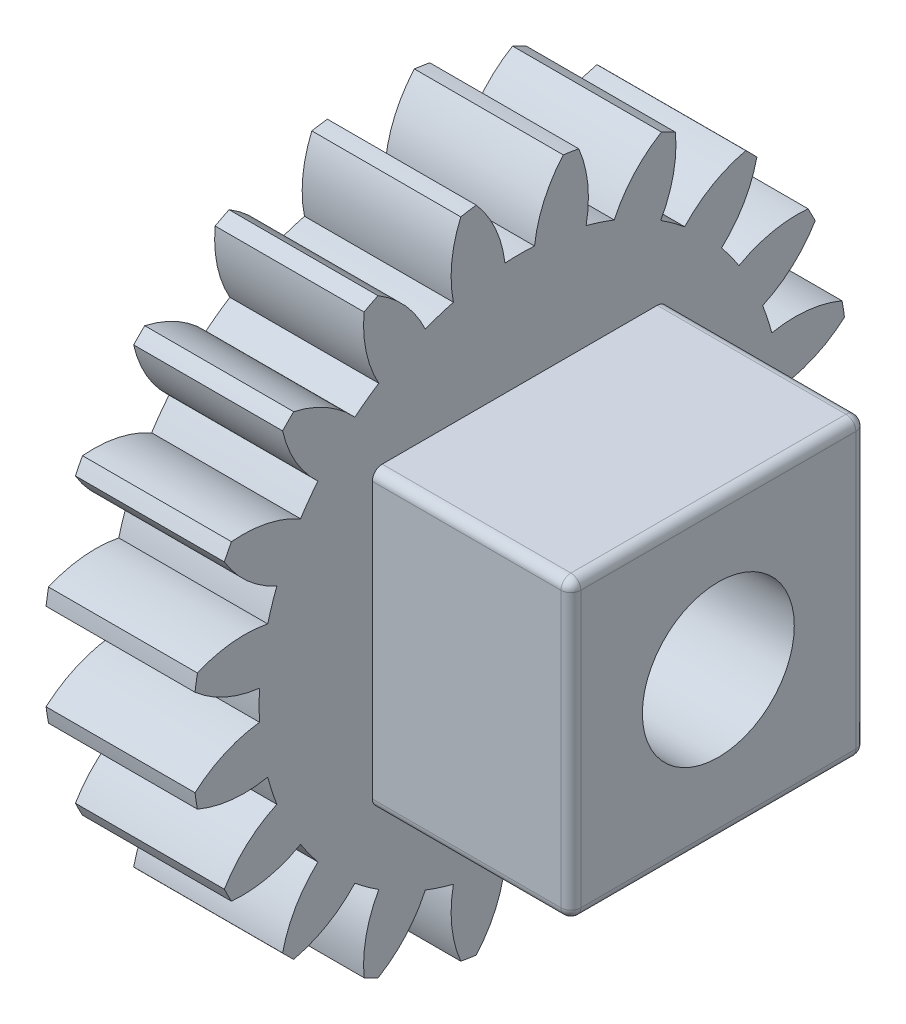
SolidWorks part; units mm, degrees
material "Custom Plastic"
ref_plane "Plane1" through (0, 0, 0) normal (0, 0, 1) x (1, 0, 0)
ref_plane "Plane2" through (0, 0, 0) normal (0, 1, 0) x (1, 0, 0)
ref_plane "Plane3" through (0, 0, 0) normal (1, 0, 0) x (0, 0, -1)
other "Configuration Table"
sketch "HoldingSke" plane through (0, 0, 0) normal (0, 1, 0) x (1, 0, 0)
  line L0 (0, 0) -> (0.3132, -0.114)
  line L1 (-15, 0) -> (100, 0) construction
  line L2 (0, 0) -> (-2.1039, 2.3779)
  line L3 (0, 0) -> (-11.863, 4.5341)
  line L4 (0, 0) -> (8.1152, 2.9537)
  line L5 (0, 0) -> (-46.8476, -17.4728)
  line L6 (0, 0) -> (-12.4344, -8.3896)
  line L7 (-2.1039, 2.3779) -> (8.6586, 51.2059)
  line L8 (-76.2, 54.61) -> (-75.5, 54.61)
  line L9 (-71.009, 38.7566) -> (-53.1078, 45.2721)
  line L10 (-76.2, 71.12) -> (104.1128, 71.12)
  line L11 (0, 0) -> (-15, 0)
  line L12 (-76.2, 101.6) -> (-76.093, 101.6)
  line L13 (24.9733, 27.94) -> (52.9518, 28.4284)
  line L14 (24.9733, 27.94) -> (24.9743, 27.94)
  line L15 (24.9733, 27.94) -> (100.4006, 29.5858)
  line L16 (-63.627, -3) -> (-12.827, -3)
  circle A0 centre (0, 0) radius 2
  circle A1 centre (0, 0) radius 26.249
  circle A2 centre (0, 0) radius 37.5
  circle A3 centre (0, 0) radius 2
  dimension "MHD" = 52.498
  dimension "Hub_dia" = 75
  dimension "Bore" = 4
  dimension "MBD" = 4
  dimension "Num_teeth" = 20
  dimension "Pitch" = 0.3333
  dimension "Overall_len" = 50
  dimension "Show_teeth" = 20
  dimension "Thickness" = 15
  dimension "OAL" = 50.0001
  dimension "T_dim" = 0.7
  dimension "Ap" = 20
  dimension "H" = 19.05
  dimension "Pitch_radius" = 180.3128
  dimension "Width" = 15
  dimension "Backlash" = 0.107
  dimension "Addendum_fac" = 1
  dimension "Dedendum_fac" = 1.25
  dimension "Clearance_fac" = 0.25
  dimension "Dedendum_add" = 0.001
  dimension "Module" = 3
sketch "BasProSke" plane through (0, 0, 0) normal (0, 1, 0) x (1, 0, 0)
  line L0 (-10, 0) -> (60, 0) construction
  line L1 (0, 0) -> (0, 33)
  line L2 (0, 0) -> (15, 0)
  line L3 (15, 0) -> (15, 33)
  line L4 (15, 33) -> (0, 33)
  dimension "Thickness" = 15
  dimension "Diameter" = 66
revolve "Base-Revolve" add sketch "BasProSke" angle 360 about L0
sketch "TooCutSke" plane through (0, 0, 0) normal (1, 0, 0) x (0, 0, -1)
  line L1 (0, 0) -> (0, 107) construction
  line L2 (0, 0) -> (-2.5409, 29.8922) construction
  line L3 (0, 0) -> (-9.3616, 59.1066) construction
  line L4 (-2.5409, 29.8922) -> (-4.6808, 29.5533) construction
  arc A0 (1.4893, 26.2067) -> (-1.4893, 26.2067) centre (0, 0) ccw
  arc A1 (4.4016, 32.7308) -> (-4.4016, 32.7308) centre (0, 0) ccw
  circle A2 centre (0, 0) radius 30 construction
  circle A3 centre (0, 0) radius 28.1908 construction
  arc A4 (-1.4893, 26.2067) -> (-4.4016, 32.7308) centre (-13.4064, 24.799) ccw
  arc A5 (4.4016, 32.7308) -> (1.4893, 26.2067) centre (13.4064, 24.799) ccw
  dimension "Root_dia" = 52.498
  dimension "Overcut_dia" = 66.0508
  dimension "Pitch_dia" = 60
  dimension "Base_dia" = 56.3816
  dimension "Flank_rad" = 12
  dimension "Half_ang" = 9
  dimension "Half_CT" = 2.1665
extrude "ToothCut" cut sketch "TooCutSke" along normal through all
fillet "Breaks" [suppressed] radius 0.06
fillet "RootFillets" [suppressed] radius 0.751
pattern_circular "TeethCuts" count 20 every 18 about axis through (-10, 0, 0) along (1, 0, 0) of "ToothCut", "RootFillets", "Breaks"
sketch "HubNeaOneSke" plane through (0, 0, 0) normal (-1, 0, 0) x (0, 0, 1)
  circle A0 centre (0, 0) radius 26.249
  dimension "Diameter" = 52.498
extrude "HubNearOne" [suppressed] add sketch "HubNeaOneSke" along normal blind 35.0001
sketch "HubNeaBotSke" plane through (0, 0, 0) normal (-1, 0, 0) x (0, 0, 1)
  circle A0 centre (0, 0) radius 26.249
  dimension "Diameter" = 52.498
extrude "HubNearBoth" [suppressed] add sketch "HubNeaBotSke" along normal blind 17.5
ref_plane "FarPln" through (15, 0, 0) normal (1, 0, 0) x (0, 0, -1)
sketch "HubFarSke" plane through (15, 0, 0) normal (1, 0, 0) x (0, 0, -1)
  circle A0 centre (0, 0) radius 26.249
  dimension "Diameter" = 52.498
extrude "HubFar" [suppressed] add sketch "HubFarSke" along normal blind 17.5
sketch "BorSke" plane through (0, 0, 0) normal (1, 0, 0) x (0, 0, -1)
  circle A0 centre (0, 0) radius 2
  dimension "Diameter" = 4
extrude "Bore" cut sketch "BorSke" along normal mid plane 100.0001
sketch "KeySke" plane through (0, 0, 0) normal (1, 0, 0) x (0, 0, -1)
  line L0 (-0.8, 0) -> (-0.8, 2.7)
  line L1 (-0.8, 2.7) -> (0.8, 2.7)
  line L2 (0.8, 2.7) -> (0.8, 0)
  line L3 (0, 0) -> (0, 34) construction
  line L4 (-0.8, 0) -> (0.8, 0)
  dimension "Offset" = 2.7
  dimension "Width" = 1.6
extrude "Keyway" [suppressed] cut sketch "KeySke" along normal mid plane 100.0001
pattern_circular "Keyway2" [suppressed] count 2 every 90 about axis through (-10, 0, 0) along (1, 0, 0)
sketch "Sketch1" plane through (15, 0, 0) normal (1, 0, 0) x (0, 0, -1)
  line L0 (-14.85, 14.85) -> (14.85, -14.85) construction
  line L1 (-14.85, 14.85) -> (14.85, 14.85)
  line L2 (-14.85, 14.85) -> (-14.85, -14.85)
  line L3 (-14.85, -14.85) -> (14.85, -14.85)
  line L4 (14.85, 14.85) -> (14.85, -14.85)
  point P4 (0, 0)
  dimension "D1" = 29.7
extrude "Boss-Extrude1" add sketch "Sketch1" along normal blind 20
sketch "Sketch2" plane through (0, 0, 0) normal (-1, 0, 0) x (0, 0, 1)
  circle A0 centre (0, 0) radius 7.65
  dimension "D1" = 15.3
extrude "Cut-Extrude1" cut sketch "Sketch2" against normal up to surface (35 mm away) contours A0 up to face at (35, 0, 0)
fillet "Fillet2" radius 1 8 edges at (35, 14.85, 0) (35, 0, 14.85) (35, -14.85, 0) (35, 0, -14.85) (25, -14.85, -14.85) (25, 14.85, -14.85) (25, 14.85, 14.85) (25, -14.85, 14.85)
equation "' \"Module@HoldingSke\" = 6.35"
equation "' \"Num_teeth@HoldingSke\" = 12"
equation "' \"Ap@HoldingSke\" =  20"
equation "' \"Ap@HoldingSke\" = 20"
equation "' \"Width@HoldingSke\" = 0.5 * 25.4"
equation "' \"Hub_dia@HoldingSke\"= 1 * 25.4"
equation "' \"Hub_dia@HoldingSke\" = 1 * 25.4"
equation "' \"Overall_len@HoldingSke\" = 1.0 * 25.4"
equation "' \"Bore@HoldingSke\" = 0.75 * 25.4"
equation "' \"T_dim@HoldingSke\" = 0.1 * 25.4"
equation "' \"Width@KeySke\" = 0.25 * 25.4"
equation "' \"Show_teeth@HoldingSke\" = 13"
equation "' \"Backlash@HoldingSke\" = 0.009 * 25.4"
equation "' \"Addendum_fac@HoldingSke\" = 1.0"
equation "' \"Dedendum_fac@HoldingSke\" = 1.25"
equation "' \"Dedendum_add@HoldingSke\" = 0.00005 * 25.4"
equation "' \"Clearance_fac@HoldingSke\" = 0.25"
equation "\"Pitch@HoldingSke\" = 1 / \"Module@HoldingSke\""
equation "\"Overcut_dia@TooCutSke\" = (\"Num_teeth@HoldingSke\" + 2 * \"Addendum_fac@HoldingSke\") / \"Pitch@HoldingSke\" + 0.002 * 25.4"
equation "\"Pitch_dia@TooCutSke\" = \"Num_teeth@HoldingSke\" / \"Pitch@HoldingSke\""
equation "\"Base_dia@TooCutSke\" = \"Num_teeth@HoldingSke\" / \"Pitch@HoldingSke\" * cos((\"Ap@HoldingSke\"  * 3.14159265 / 180))"
equation "\"Root_dia@TooCutSke\" = (\"Num_teeth@HoldingSke\" + 2) / \"Pitch@HoldingSke\" - 2 * (\"Addendum_fac@HoldingSke\" + \"Dedendum_fac@HoldingSke\") / \"Pitch@HoldingSke\" - \"Dedendum_add@HoldingSke\" * 2"
equation "\"Half_ang@TooCutSke\" = 180 / \"Num_teeth@HoldingSke\""
equation "\"Half_CT@TooCutSke\" = \"Num_teeth@HoldingSke\" / \"Pitch@HoldingSke\" * sin((3.14159265 / 2 / \"Num_teeth@HoldingSke\")) / 2 - 7 * \"Backlash@HoldingSke\" / 4"
equation "\"Flank_rad@TooCutSke\" = \"Num_teeth@HoldingSke\" / \"Pitch@HoldingSke\" / 5"
equation "\"Radius@RootFillets\" = \"Clearance_fac@HoldingSke\" / \"Pitch@HoldingSke\" + \"Dedendum_add@HoldingSke\""
equation "\"Break_rad@Breaks\" = 0.02 / \"Pitch@HoldingSke\""
equation "\"Thickness@HoldingSke\" = \"Width@HoldingSke\""
equation "\"OAL@HoldingSke\" = \"Thickness@HoldingSke\""
equation "\"MHD@HoldingSke\" = (\"Num_teeth@HoldingSke\" + 2) / \"Pitch@HoldingSke\" - 2 * (\"Addendum_fac@HoldingSke\" + \"Dedendum_fac@HoldingSke\")  / \"Pitch@HoldingSke\" - \"Dedendum_add@HoldingSke\" * 2"
equation "\"MBD@HoldingSke\" = (\"Num_teeth@HoldingSke\" + 2) / \"Pitch@HoldingSke\" - 2 * (\"Addendum_fac@HoldingSke\" + \"Dedendum_fac@HoldingSke\")  / \"Pitch@HoldingSke\" - \"Dedendum_add@HoldingSke\" * 2 - 0.002 * 25.4"
equation "\"MHD@HoldingSke\" = ((sgn( \"MHD@HoldingSke\" - \"Hub_dia@HoldingSke\" )-1)*( \"MHD@HoldingSke\" - \"Hub_dia@HoldingSke\" ))/-2+ \"Hub_dia@HoldingSke\""
equation "\"MBD@HoldingSke\" = ((sgn( \"MBD@HoldingSke\" - \"Bore@HoldingSke\" )-1)*( \"MBD@HoldingSke\" - \"Bore@HoldingSke\" ))/-2+ \"Bore@HoldingSke\""
equation "\"OAL@HoldingSke\" = ((sgn( \"OAL@HoldingSke\" - \"Overall_len@HoldingSke\" )+1)*( \"OAL@HoldingSke\" - \"Overall_len@HoldingSke\" ))/2 + \"Overall_len@HoldingSke\" + 0.000002 * 25.4"
equation "\"Num_teeth@TeethCuts\" = int( \"Show_teeth@HoldingSke\" ) + 1"
equation "\"Num_teeth@TeethCuts\" = ((sgn( \"Num_teeth@TeethCuts\" - \"Num_teeth@HoldingSke\" )-1)*( \"Num_teeth@TeethCuts\" - \"Num_teeth@HoldingSke\" ))/-2+ \"Num_teeth@HoldingSke\""
equation "\"Num_teeth@TeethCuts\" = ((sgn( \"Num_teeth@TeethCuts\" - 2.0)+1)*( \"Num_teeth@TeethCuts\" - 2.0))/2 +2.0"
equation "\"Angle@TeethCuts\" = 360.0 / \"Num_teeth@HoldingSke\""
equation "\"Diameter@BasProSke\" = (\"Num_teeth@HoldingSke\" + 2 * \"Addendum_fac@HoldingSke\") / \"Pitch@HoldingSke\""
equation "\"Thickness@BasProSke\"  = \"Thickness@HoldingSke\""
equation "' \"Fillet_rad@BasProSke\" =  \"Thickness@HoldingSke\" * 0.05"
equation "' \"Fillet_rad@BasProSke\" = \"Thickness@HoldingSke\" * 0.05"
equation "\"MHD@HoldingSke\" = ((sgn( \"MHD@HoldingSke\" - \"Root_dia@TooCutSke\" )-1)*( \"MHD@HoldingSke\" - \"Root_dia@TooCutSke\" ))/-2+ \"Root_dia@TooCutSke\""
equation "\"Diameter@HubNeaOneSke\" = \"MHD@HoldingSke\""
equation "\"Length@HubNearOne\" = \"OAL@HoldingSke\" - \"Thickness@BasProSke\""
equation "\"Diameter@HubNeaBotSke\" = \"MHD@HoldingSke\""
equation "\"Length@HubNearBoth\" = ( \"OAL@HoldingSke\" - \"Thickness@BasProSke\" ) / 2.0"
equation "\"Thickness@FarPln\" = \"Thickness@BasProSke\""
equation "\"Diameter@HubFarSke\" = \"MHD@HoldingSke\""
equation "\"Length@HubFar\" = ( \"OAL@HoldingSke\" - \"Thickness@BasProSke\" ) / 2.0"
equation "\"Diameter@BorSke\" = \"MBD@HoldingSke\""
equation "\"D1@Bore\" = \"OAL@HoldingSke\" * 2.0"
equation "\"D1@Keyway\" = \"OAL@HoldingSke\" * 2.0"
equation "\"Offset@KeySke\" = \"T_dim@HoldingSke\" + \"MBD@HoldingSke\" / 2.0"
